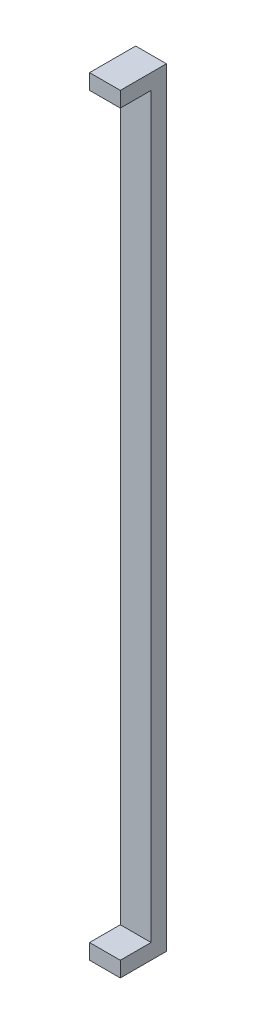
SolidWorks part; units mm, degrees
ref_plane "Спереди" through (0, 0, 0) normal (0, 0, 1) x (1, 0, 0)
ref_plane "Сверху" through (0, 0, 0) normal (0, 1, 0) x (1, 0, 0)
ref_plane "Справа" through (0, 0, 0) normal (1, 0, 0) x (0, 0, -1)
sketch "Эскиз1" plane through (0, 0, 0) normal (1, 0, 0) x (0, 0, -1)
  line L0 (0, 0) -> (0, 1000) construction
  line L1 (0, 0) -> (60, 0)
  line L2 (60, 0) -> (60, 1000)
  line L3 (60, 1000) -> (0, 1000)
  line L4 (0, 0) -> (0, 20)
  line L5 (0, 20) -> (40, 20)
  line L6 (40, 20) -> (40, 980)
  line L7 (40, 980) -> (0, 980)
  line L8 (0, 980) -> (0, 1000)
  line L9 (40, 980) -> (60, 980) construction
  dimension "D1" = 20
  dimension "D2" = 1000
  dimension "D3" = 60
extrude "Бобышка-Вытянуть1" add sketch "Эскиз1" along normal blind 40
